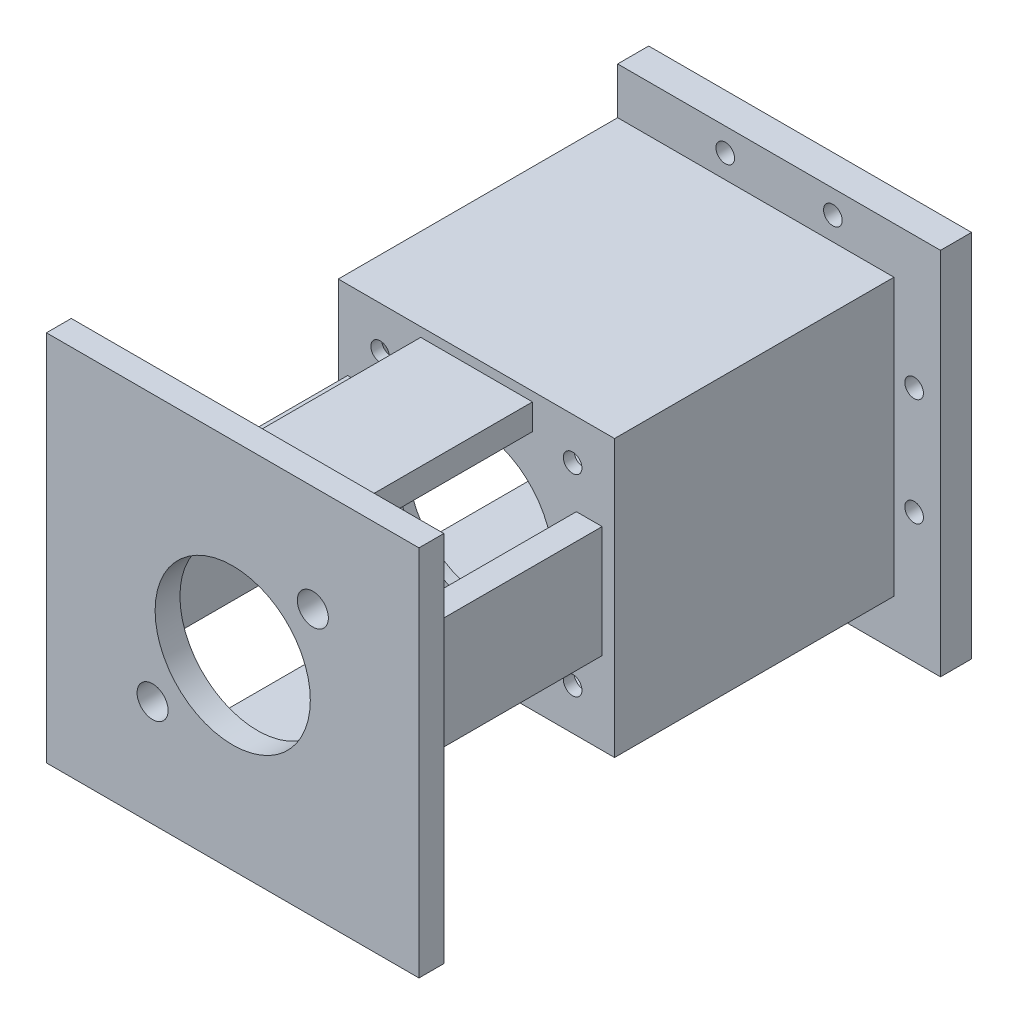
SolidWorks part; units mm, degrees
ref_plane "Front Plane" through (0, 0, 0) normal (0, 0, 1) x (1, 0, 0)
ref_plane "Top Plane" through (0, 0, 0) normal (0, 1, 0) x (1, 0, 0)
ref_plane "Right Plane" through (0, 0, 0) normal (1, 0, 0) x (0, 0, -1)
sketch "Sketch6" plane through (0, 0, 0) normal (0, 0, 1) x (1, 0, 0)
  line L1 (-482.0212, -225.0811) -> (-437.5212, -225.0811)
  line L2 (-482.0212, -225.0811) -> (-482.0212, -180.5811)
  line L3 (-482.0212, -180.5811) -> (-437.5212, -180.5811)
  line L4 (-437.5212, -225.0811) -> (-437.5212, -180.5811)
  line L8 (-430.0212, -232.5811) -> (-430.0212, -173.0811)
  line L9 (-482.0212, -173.0811) -> (-430.0212, -173.0811)
  line L10 (-482.0212, -173.0811) -> (-482.0212, -232.5811)
  line L11 (-482.0212, -232.5811) -> (-430.0212, -232.5811)
  line L12 (-430.0212, -173.0811) -> (-430.0212, -232.5811)
  circle A0 centre (-460.0212, -202.5811) radius 12.5
  circle A1 centre (-475.2712, -187.3311) radius 1.5
  circle A2 centre (-444.2712, -187.3311) radius 1.5
  circle A3 centre (-444.2712, -218.3311) radius 1.5
  circle A4 centre (-475.2712, -218.3311) radius 1.5
  circle A8 centre (-464.6879, -228.3311) radius 1.5
  circle A9 centre (-447.3545, -228.3311) radius 1.5
  circle A12 centre (-447.3546, -176.8311) radius 1.5
  circle A13 centre (-464.6879, -176.8311) radius 1.5
  circle A14 centre (-434.2712, -211.7157) radius 1.5
  circle A15 centre (-434.2712, -194.3823) radius 1.5
  point P29 (-460.0212, -202.5811)
  point P38 (-456.0212, -202.5811)
  dimension "D9" = 25
  dimension "D10" = 3
  dimension "D7" = 22
  dimension "D15" = 17.3333
  dimension "D3" = 3
  dimension "D1" = 44.5
  dimension "D2" = 44.5
  dimension "D4" = 7.5
  dimension "D5" = 17.3333
  dimension "D6" = 17.3333
  dimension "D8" = 22
  dimension "D11" = 6.75
  dimension "D14" = 6.75
  dimension "D16" = 17.3333
  dimension "D17" = 3.25
  dimension "D19" = 52
  dimension "D20" = 3.25
  dimension "D18" = 3.25
  dimension "D12" = 2
  dimension "D13" = 2
sketch "Sketch7" plane through (0, 0, 0) normal (0, 0, 1) x (1, 0, 0)
  line L0 (-437.5212, -225.0811) -> (-437.5212, -180.5811) construction
  line L1 (-482.0212, -224.0811) -> (-438.5212, -224.0811)
  line L2 (-482.0212, -224.0811) -> (-482.0212, -181.5811)
  line L3 (-482.0212, -181.5811) -> (-438.5212, -181.5811)
  line L4 (-438.5212, -224.0811) -> (-438.5212, -181.5811)
  line L5 (-482.0212, -180.5811) -> (-437.5212, -180.5811) construction
  dimension "D3" = 43.5
  dimension "D4" = 42.5
  dimension "D5" = 1
  dimension "D6" = 1
sketch "Sketch8" plane through (0, 0, 0) normal (0, 0, 1) x (1, 0, 0)
  line L1 (-482.0212, -225.0811) -> (-437.5212, -225.0811)
  line L2 (-482.0212, -225.0811) -> (-482.0212, -180.5811)
  line L3 (-482.0212, -180.5811) -> (-437.5212, -180.5811)
  line L4 (-437.5212, -225.0811) -> (-437.5212, -180.5811)
  line L5 (-489.5212, -232.5811) -> (-430.0212, -232.5811)
  line L6 (-489.5212, -232.5811) -> (-489.5212, -173.0811)
  line L7 (-489.5212, -173.0811) -> (-430.0212, -173.0811)
  line L8 (-430.0212, -232.5811) -> (-430.0212, -173.0811)
  circle A0 centre (-460.0212, -202.5811) radius 12.5
  circle A1 centre (-475.2712, -187.3311) radius 1.5
  circle A2 centre (-444.2712, -187.3311) radius 1.5
  circle A3 centre (-444.2712, -218.3311) radius 1.5
  circle A4 centre (-475.2712, -218.3311) radius 1.5
  dimension "D9" = 25
  dimension "D10" = 3
  dimension "D7" = 22
  dimension "D1" = 44.5
  dimension "D2" = 44.5
  dimension "D3" = 7.5
  dimension "D4" = 7.5
  dimension "D5" = 7.5
  dimension "D6" = 7.5
  dimension "D8" = 22
  dimension "D11" = 6.75
  dimension "D14" = 6.75
  dimension "D12" = 2
  dimension "D13" = 2
extrude "Boss-Extrude4" add sketch "Sketch6" along normal blind 5
extrude "Boss-Extrude5" add sketch "Sketch8" along normal blind 50 contours L1 L4 L3 L2 A4 A3 A2 A1 A0
extrude "Cut-Extrude4" cut sketch "Sketch7" along normal blind 48.25
sketch "Sketch10" plane through (-482.0212, 0, 0) normal (-1, 0, 0) x (0, 0, 1)
  line L0 (24.125, -181.5811) -> (48.25, -224.0811)
  line L1 (48.25, -181.5811) -> (0, -181.5811) construction
  line L2 (48.25, -224.0811) -> (48.25, -181.5811)
  line L3 (48.25, -181.5811) -> (24.125, -181.5811)
extrude "Boss-Extrude6" add sketch "Sketch10" against normal blind 1
sketch "Sketch11" plane through (0, 0, 50) normal (0, 0, 1) x (1, 0, 0)
  line L1 (-469.3031, -223.0811) -> (-469.3031, -218.9311)
  line L2 (-439.5212, -193.863) -> (-443.6712, -193.863)
  line L3 (-439.5212, -193.863) -> (-439.5212, -211.863)
  line L4 (-439.5212, -211.863) -> (-443.6712, -211.863)
  line L5 (-443.6712, -193.863) -> (-443.6712, -211.863)
  line L6 (-451.3031, -223.0811) -> (-469.3031, -223.0811)
  line L7 (-451.3031, -218.9311) -> (-469.3031, -218.9311)
  line L8 (-451.3031, -223.0811) -> (-451.3031, -218.9311)
  line L9 (-480.5212, -193.2993) -> (-476.3712, -193.2993)
  line L10 (-480.5212, -211.2993) -> (-480.5212, -193.2993)
  line L11 (-476.3712, -211.2993) -> (-476.3712, -193.2993)
  line L12 (-480.5212, -211.2993) -> (-476.3712, -211.2993)
  line L13 (-450.7394, -182.0811) -> (-450.7394, -186.2311)
  line L14 (-468.7394, -182.0811) -> (-450.7394, -182.0811)
  line L15 (-468.7394, -186.2311) -> (-450.7394, -186.2311)
  line L16 (-468.7394, -182.0811) -> (-468.7394, -186.2311)
  point P21 (-460.0212, -202.5811)
  dimension "D1" = 18
  dimension "D3" = 20.5
  dimension "D4" = 16.35
  dimension "D2" = 4
extrude "Boss-Extrude7" add sketch "Sketch11" along normal blind 35
sketch "Sketch13" plane through (0, 0, 0) normal (0, 0, 1) x (1, 0, 0)
  point P0 (-460.0212, -202.5811)
sketch "Sketch14" plane through (0, 0, 85) normal (0, 0, 1) x (1, 0, 0)
  line L1 (-430.0212, -172.5811) -> (-490.0212, -172.5811)
  line L2 (-430.0212, -172.5811) -> (-430.0212, -232.5811)
  line L3 (-430.0212, -232.5811) -> (-490.0212, -232.5811)
  line L4 (-490.0212, -172.5811) -> (-490.0212, -232.5811)
  dimension "D1" = 60
  dimension "D2" = 60
  dimension "D3" = 30
  dimension "D4" = 30
extrude "Boss-Extrude8" add sketch "Sketch14" along normal blind 4
sketch "Sketch16" plane through (0, 0, 89) normal (0, 0, 1) x (1, 0, 0)
  line L1 (-490.0212, -232.5811) -> (-430.0212, -232.5811) construction
  line L4 (-490.0212, -172.5811) -> (-490.0212, -232.5811) construction
  circle A3 centre (-447.1165, -189.6764) radius 2.5
  circle A4 centre (-472.9259, -215.4858) radius 2.5
  point P7 (-460.0212, -202.5811)
  dimension "D1" = 5
  dimension "D5" = 30
  dimension "D6" = 30
  dimension "D7" = 36.5
  dimension "D4" = 2
extrude "Cut-Extrude5" cut sketch "Sketch16" against normal up to next
sketch "Sketch17" plane through (0, 0, 0) normal (0, 0, 1) x (1, 0, 0)
  line L1 (-482.0212, -225.0811) -> (-437.5212, -225.0811)
  line L2 (-482.0212, -225.0811) -> (-482.0212, -180.5811)
  line L3 (-482.0212, -180.5811) -> (-437.5212, -180.5811)
  line L4 (-437.5212, -225.0811) -> (-437.5212, -180.5811)
  line L5 (-489.5212, -232.5811) -> (-430.0212, -232.5811)
  line L6 (-489.5212, -232.5811) -> (-489.5212, -173.0811)
  line L7 (-489.5212, -173.0811) -> (-430.0212, -173.0811)
  line L8 (-430.0212, -232.5811) -> (-430.0212, -173.0811)
  circle A0 centre (-460.0212, -202.5811) radius 12.5
  circle A1 centre (-475.2712, -187.3311) radius 1.5
  circle A2 centre (-444.2712, -187.3311) radius 1.5
  circle A3 centre (-444.2712, -218.3311) radius 1.5
  circle A4 centre (-475.2712, -218.3311) radius 1.5
  dimension "D9" = 25
  dimension "D10" = 3
  dimension "D7" = 22
  dimension "D1" = 44.5
  dimension "D2" = 44.5
  dimension "D3" = 7.5
  dimension "D4" = 7.5
  dimension "D5" = 7.5
  dimension "D6" = 7.5
  dimension "D8" = 22
  dimension "D11" = 6.75
  dimension "D14" = 6.75
  dimension "D12" = 2
  dimension "D13" = 2
extrude "Cut-Extrude6" cut sketch "Sketch17" along normal through all contours A0
